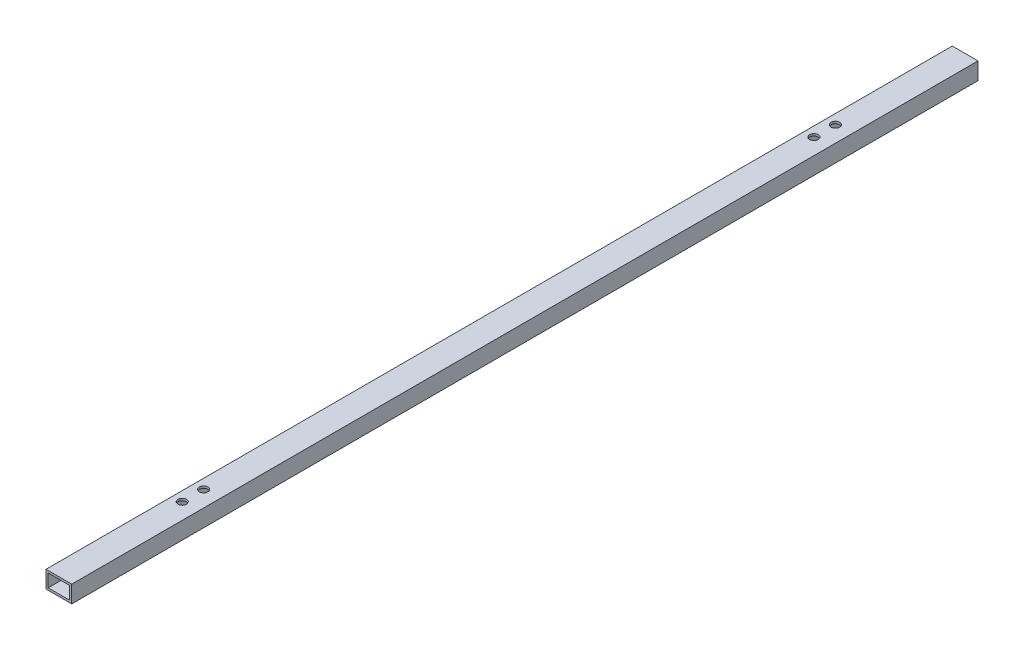
SolidWorks part; units mm, degrees
material "6061 Alloy"
ref_plane "Front Plane" through (0, 0, 0) normal (0, 0, 1) x (1, 0, 0)
ref_plane "Top Plane" through (0, 0, 0) normal (0, 1, 0) x (1, 0, 0)
ref_plane "Right Plane" through (0, 0, 0) normal (1, 0, 0) x (0, 0, -1)
sketch "Sketch1" plane through (0, 0, 0) normal (0, 0, 1) x (1, 0, 0)
  line L0 (19.05, 0) -> (15.875, 0) construction
  line L1 (-19.05, 0) -> (19.05, 0) construction
  line L2 (0, 12.7) -> (0, -12.7)
  point P7 (0, 0)
sketch "Sketch2" plane through (0, 0, 0) normal (1, 0, 0) x (0, 0, -1)
  line L0 (670.56, 0) -> (-670.56, 0)
  point P4 (0, 0)
  dimension "Length" = 1341.12
sketch "Sketch3" plane through (0, 0, 0) normal (0, 0, 1) x (1, 0, 0)
  line L0 (-19.05, 0) -> (19.05, 0) construction
  line L5 (19.05, -12.7) -> (-19.05, -12.7)
  line L6 (19.05, -12.7) -> (19.05, 12.7)
  line L11 (19.05, 12.7) -> (-19.05, 12.7)
  line L12 (-19.05, -12.7) -> (-19.05, 12.7)
  line L14 (19.05, -12.7) -> (-19.05, 12.7) construction
  line L15 (19.05, 12.7) -> (-19.05, -12.7) construction
  line L16 (15.875, -9.525) -> (-15.875, -9.525)
  line L17 (15.875, -9.525) -> (15.875, 9.525)
  line L18 (15.875, 9.525) -> (-15.875, 9.525)
  line L19 (-15.875, -9.525) -> (-15.875, 9.525)
  line L20 (15.875, -9.525) -> (-15.875, 9.525) construction
  line L21 (15.875, 9.525) -> (-15.875, -9.525) construction
  point P0 (0, 0)
  point P5 (0, 0)
  point P13 (15.875, -12.7)
  dimension "D1" = 3.175
  dimension "D3" = 38.1
  dimension "D4" = 25.4
  dimension "D2" = 3.175
extrude "Boss-Extrude1" add sketch "Sketch3" along normal up to vertex (670.56 mm away) and the other way up to vertex (670.56 mm away) up to point (0, 0, 670.56) other way up to point (0, 0, -670.56)
sketch "Sketch5" plane through (0, 0, 0) normal (1, 0, 0) x (0, 0, -1)
  line L0 (-670.56, 0) -> (670.56, 0) construction
  line L3 (-670.56, -12.7) -> (-670.56, 12.7) construction
  line L4 (670.56, -12.7) -> (670.56, 12.7) construction
  point P6 (-627.6975, 0)
  point P7 (-613.41, 0)
  point P8 (613.41, 0)
  point P10 (627.6975, 0)
  dimension "D1" = 42.8625
  dimension "D2" = 57.15
  dimension "D3" = 42.8625
  dimension "D4" = 57.15
sketch "Sketch6" plane through (0, 12.7, 0) normal (0, 1, 0) x (1, 0, 0)
  line L0 (19.05, 670.56) -> (-19.05, 670.56) construction
  line L1 (-19.05, 0) -> (19.05, 0) construction
  line L2 (-19.05, -670.56) -> (-19.05, 670.56) construction
  line L3 (19.05, -670.56) -> (19.05, 670.56) construction
  line L4 (-15.875, -670.56) -> (-15.875, 670.56)
  line L5 (-15.875, -670.56) -> (-15.875, 670.56)
  line L6 (-15.875, 467.36) -> (6.35, 467.36) construction
  line L7 (6.35, -670.56) -> (6.35, 670.56)
  line L8 (6.35, -670.56) -> (6.35, 670.56)
  line L9 (-4.7625, 467.36) -> (-4.7625, 499.11) construction
  circle A0 centre (-4.7625, 483.235) radius 6.35
  circle A1 centre (-4.7625, 451.485) radius 6.35
  circle A2 centre (-4.7625, -483.235) radius 6.35
  circle A3 centre (-4.7625, -451.485) radius 6.35
  dimension "D1" = 203.2
  dimension "D4" = 31.75
  dimension "D2" = 3.175
  dimension "D3" = 12.7
extrude "Cut-Extrude1" cut sketch "Sketch6" against normal through all contours A3 | A2 | A0 | A1
equation "\"D1@Sketch3\"=\"Wall thickness@Sketch1\""
equation "\"D1@Sketch5\"=\"Width@Sketch1\"*1.125"
equation "\"D2@Sketch5\"=\"Width@Sketch1\"*1.5"
equation "\"D3@Sketch5\"=\"D1@Sketch5\""
equation "\"D4@Sketch5\"=\"D2@Sketch5\""
equation "\"D2@Sketch3\"=\"Wall Thickness@Sketch1\""
